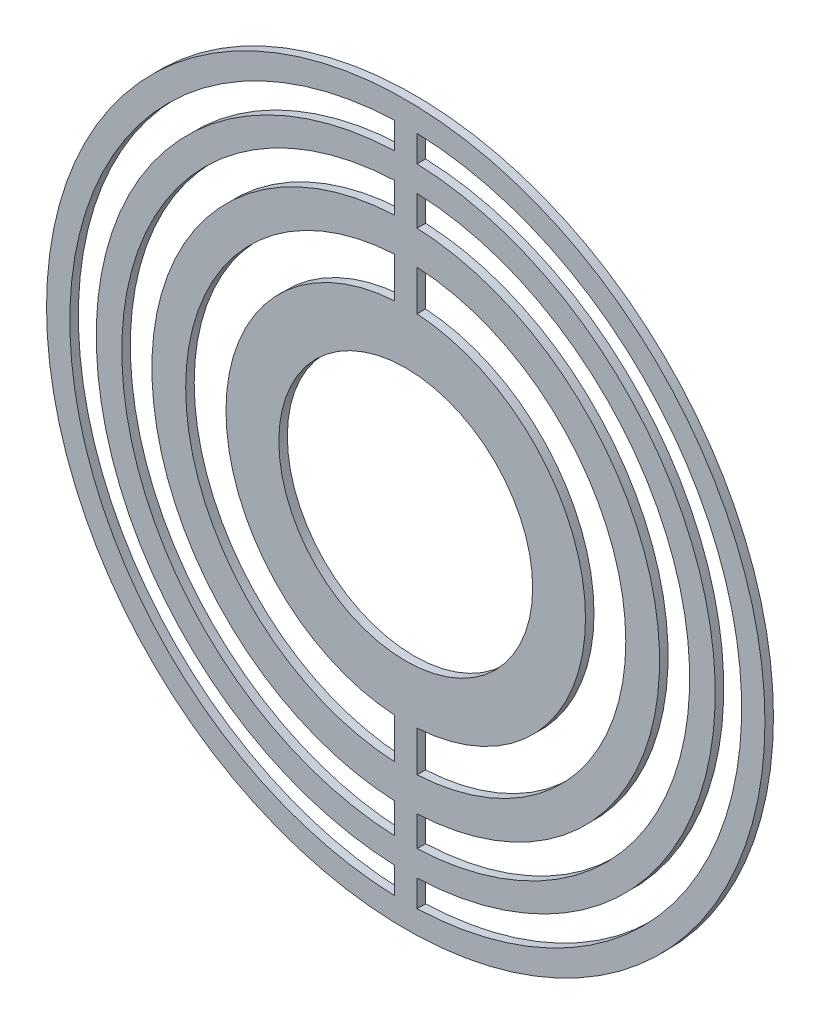
SolidWorks part; units mm, degrees
ref_plane "前视基准面" through (0, 0, 0) normal (0, 0, 1) x (1, 0, 0)
ref_plane "上视基准面" through (0, 0, 0) normal (0, 1, 0) x (1, 0, 0)
ref_plane "右视基准面" through (0, 0, 0) normal (1, 0, 0) x (0, 0, -1)
other "Configuration Table"
sketch "草图1" plane through (0, 0, 0) normal (0, 0, 1) x (1, 0, 0)
  line L0 (-4, 118.2324) -> (-4, 108.9266)
  line L1 (4, 118.2324) -> (4, 108.9266)
  line L2 (4, -63.1735) -> (4, -77.3967)
  line L3 (-4, -63.1735) -> (-4, -77.3967)
  line L4 (-4, 99.92) -> (-4, 89.3105)
  line L5 (4, 99.92) -> (4, 89.3105)
  line L6 (4, 77.3967) -> (4, 63.1735)
  line L7 (-4, 77.3967) -> (-4, 63.1735)
  line L9 (-4, -108.9266) -> (-4, -118.2324)
  line L10 (4, -108.9266) -> (4, -118.2324)
  line L11 (-4, -89.3105) -> (-4, -99.92)
  line L12 (4, -89.3105) -> (4, -99.92)
  circle A0 centre (0, 0) radius 44.7
  arc A1 (-4, 63.1735) -> (-4, -63.1735) centre (0, 0) ccw
  arc A2 (-4, 77.3967) -> (-4, -77.3967) centre (0, 0) ccw
  arc A3 (-4, 89.3105) -> (-4, -89.3105) centre (0, 0) ccw
  arc A4 (-4, 99.92) -> (-4, -99.92) centre (0, 0) ccw
  arc A5 (-4, 108.9266) -> (-4, -108.9266) centre (0, 0) ccw
  arc A6 (-4, 118.2324) -> (-4, -118.2324) centre (0, 0) ccw
  circle A7 centre (0, 0) radius 126.5
  arc A8 (4, -63.1735) -> (4, 63.1735) centre (0, 0) ccw
  arc A9 (4, -77.3967) -> (4, 77.3967) centre (0, 0) ccw
  arc A10 (4, -89.3105) -> (4, 89.3105) centre (0, 0) ccw
  arc A11 (4, -99.92) -> (4, 99.92) centre (0, 0) ccw
  arc A12 (4, -108.9266) -> (4, 108.9266) centre (0, 0) ccw
  arc A13 (4, -118.2324) -> (4, 118.2324) centre (0, 0) ccw
  dimension "D1" = 89.4
  dimension "D2" = 126.6
  dimension "D3" = 155
  dimension "D4" = 178.8
  dimension "D5" = 200
  dimension "D6" = 218
  dimension "D7" = 236.6
  dimension "D8" = 253
  dimension "D9" = 4
  dimension "D10" = 4
extrude "凸台-拉伸1" add sketch "草图1" along normal blind 3
